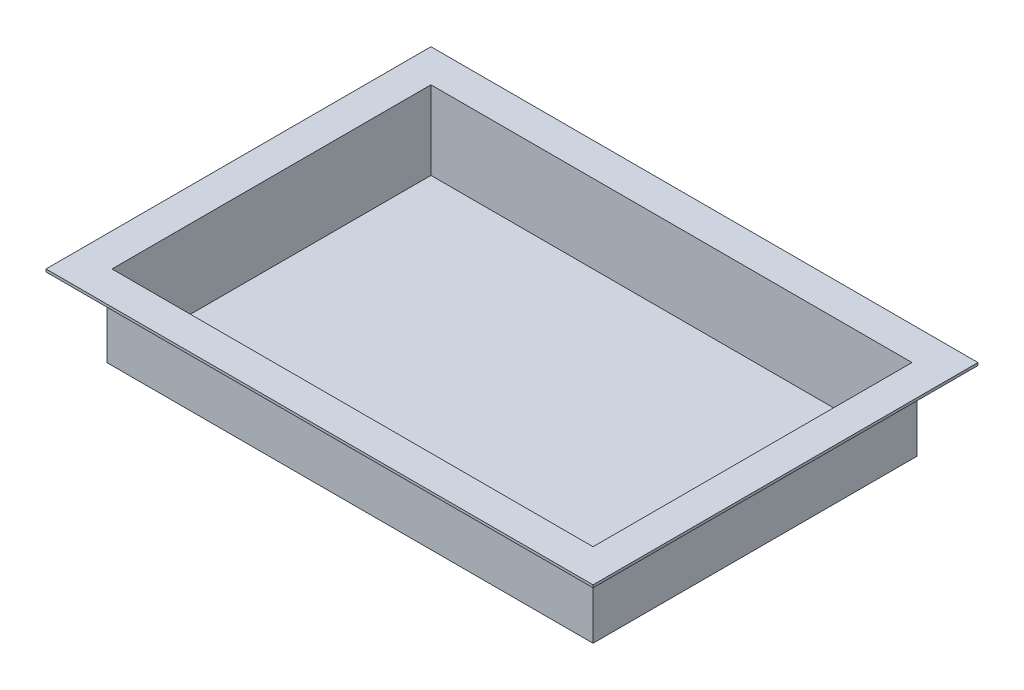
SolidWorks part; units mm, degrees
ref_plane "Front Plane" through (0, 0, 0) normal (0, 0, 1) x (1, 0, 0)
ref_plane "Top Plane" through (0, 0, 0) normal (0, 1, 0) x (1, 0, 0)
ref_plane "Right Plane" through (0, 0, 0) normal (1, 0, 0) x (0, 0, -1)
sketch "Sketch1" plane through (0, 0, 0) normal (0, 1, 0) x (1, 0, 0)
  line L1 (-76.2, 50.8) -> (76.2, 50.8)
  line L2 (-76.2, 50.8) -> (-76.2, -50.8)
  line L3 (-76.2, -50.8) -> (76.2, -50.8)
  line L4 (76.2, 50.8) -> (76.2, -50.8)
  line L5 (-76.2, 50.8) -> (76.2, -50.8) construction
  line L6 (-76.2, -50.8) -> (76.2, 50.8) construction
  point P0 (0, 0)
  dimension "D1" = 152.4
  dimension "D2" = 101.6
extrude "Boss-Extrude1" add sketch "Sketch1" against normal blind 25.4
sketch "Sketch3" plane through (0, 0, 0) normal (0, 1, 0) x (1, 0, 0)
  line L0 (-76.2, -50.8) -> (76.2, -50.8) construction
  line L1 (76.2, -50.8) -> (76.2, 50.8) construction
  line L2 (76.2, 50.8) -> (-76.2, 50.8) construction
  line L3 (-76.2, 50.8) -> (-76.2, -50.8) construction
  line L4 (-76.2, -50.8) -> (76.2, -50.8)
  line L5 (76.2, -50.8) -> (76.2, 50.8)
  line L6 (76.2, 50.8) -> (-76.2, 50.8)
  line L7 (-76.2, 50.8) -> (-76.2, -50.8)
  line L8 (-85.725, 60.325) -> (-85.725, -60.325)
  line L9 (-85.725, -60.325) -> (85.725, -60.325)
  line L10 (85.725, -60.325) -> (85.725, 60.325)
  line L11 (85.725, 60.325) -> (-85.725, 60.325)
  dimension "D1" = 9.525
shell "Shell1" thickness 0.8128
extrude "Boss-Extrude2" add sketch "Sketch3" against normal blind 0.8128
sketch "Sketch4" plane through (0, 0, 0) normal (0, 1, 0) x (1, 0, 0)
  line L0 (-75.3872, -49.9872) -> (-85.725, -60.325)
  line L1 (-75.3872, 49.9872) -> (-85.725, 60.325)
  line L2 (75.3872, 49.9872) -> (85.725, 60.325)
  line L3 (75.3872, -49.9872) -> (85.725, -60.325)
